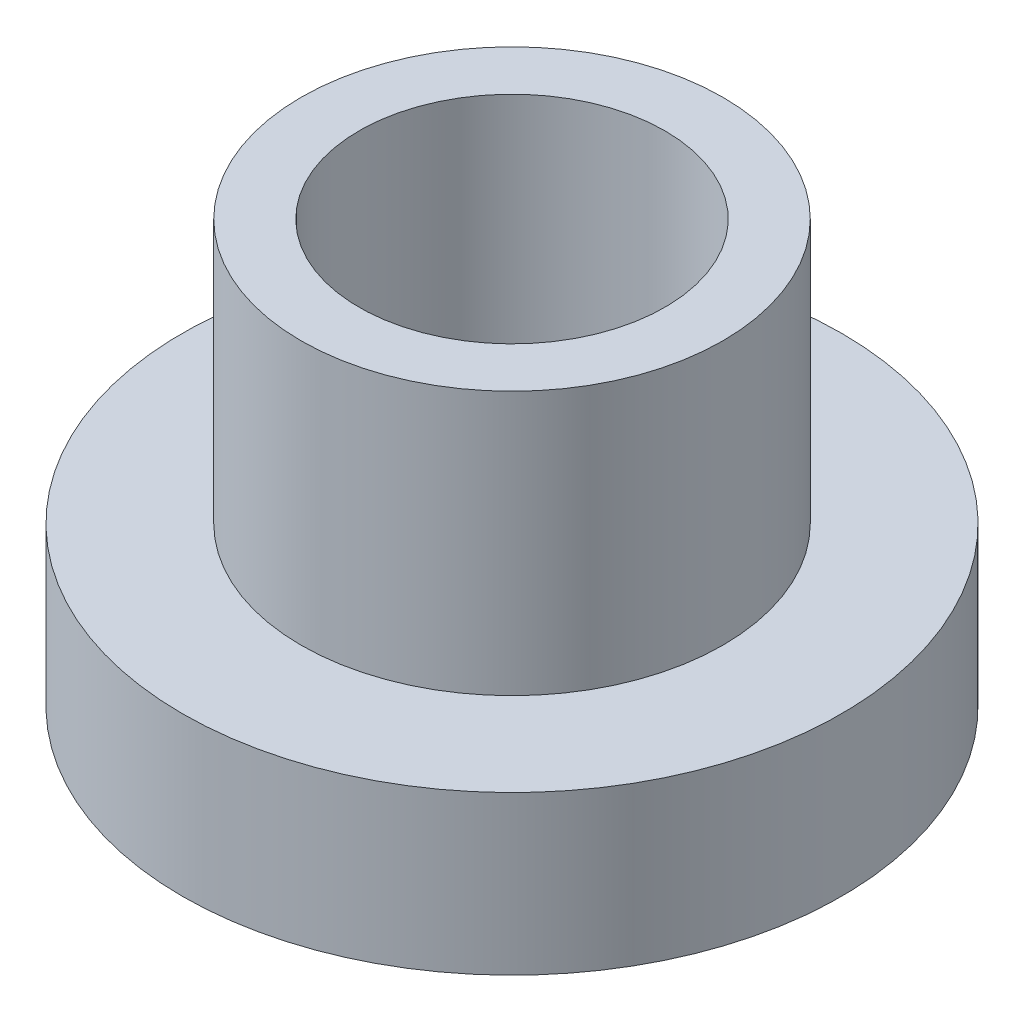
SolidWorks part; units mm, degrees
ref_plane "Płaszczyzna przednia" through (0, 0, 0) normal (0, 0, 1) x (1, 0, 0)
ref_plane "Płaszczyzna górna" through (0, 0, 0) normal (0, 1, 0) x (1, 0, 0)
ref_plane "Płaszczyzna prawa" through (0, 0, 0) normal (1, 0, 0) x (0, 0, -1)
sketch "Sketch1" plane through (0, 0, 0) normal (0, 1, 0) x (1, 0, 0)
  circle A0 centre (0, 0) radius 4
  dimension "D1" = 8
extrude "Boss-Extrude1" add sketch "Sketch1" along normal blind 5
sketch "Sketch2" plane through (0, 0, 0) normal (0, -1, 0) x (1, 0, 0)
  circle A0 centre (0, 0) radius 6.25
  dimension "D1" = 12.5
extrude "Boss-Extrude2" add sketch "Sketch2" along normal blind 3
sketch "Sketch3" plane through (0, 5, 0) normal (0, 1, 0) x (1, 0, 0)
  circle A0 centre (0, 0) radius 2.8
  dimension "D1" = 5.6
extrude "Cut-Extrude1" cut sketch "Sketch3" against normal through all
hole_wizard "CSK for M5 Hex Socket Countersunk Head Screw1" positions "Sketch4" profile "Sketch5" countersink size "M5" standard "DIN" end condition through all
sketch "Sketch4" plane through (0, -3, 0) normal (0, -1, 0) x (-1, 0, 0)
  point P0 (0, 0)
sketch "Sketch5" plane through (0, -3, 0) normal (1, 0, 0) x (0, 0, -1)
  line L0 (0, 0) -> (0, 8)
  line L1 (0, 8) -> (2.9, 8)
  line L2 (2.9, 8) -> (2.9, 2.835)
  line L3 (2.9, 2.835) -> (5.735, 0)
  line L5 (5.735, 0) -> (0, 0)
  line L6 (-2.9, 2.835) -> (-5.735, 0) construction
  line L11 (0, -6.35) -> (0, 107.95) construction
  dimension "Thru Hole Dia." = 5.8
  dimension "Thru Hole Depth" = 8
  dimension "Near C'Sink Dia." = 11.47
  dimension "Near C'Sink Angle" = 90
